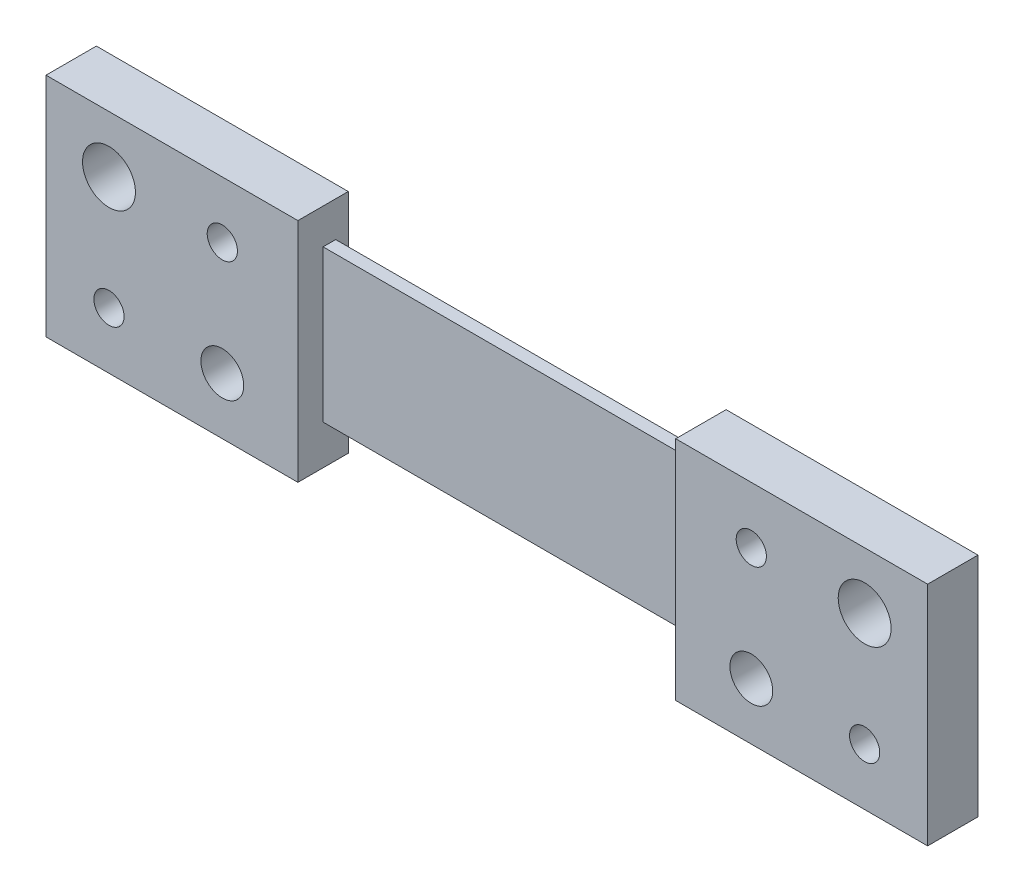
SolidWorks part; units mm, degrees
ref_plane "Спереди" through (0, 0, 0) normal (0, 0, 1) x (1, 0, 0)
ref_plane "Сверху" through (0, 0, 0) normal (0, 1, 0) x (1, 0, 0)
ref_plane "Справа" through (0, 0, 0) normal (1, 0, 0) x (0, 0, -1)
sketch "Эскиз1" plane through (0, 0, 0) normal (0, 0, 1) x (1, 0, 0)
  line L0 (-42.678, 0) -> (49.8614, 0) construction
  line L1 (0, 35.1777) -> (0, -24.4025) construction
  line L2 (15, -9) -> (15, 9)
  line L3 (-35, -9) -> (-15, -9)
  line L4 (-35, -9) -> (-35, 9)
  line L5 (-35, 9) -> (-15, 9)
  line L6 (-15, -9) -> (-15, 9)
  line L7 (35, 9) -> (15, 9)
  line L8 (35, -9) -> (35, 9)
  line L9 (35, -9) -> (15, -9)
  circle A0 centre (-30, 4.5) radius 2.1
  circle A1 centre (-21, 4.5) radius 1.2
  circle A2 centre (-21, -4.5) radius 1.7
  circle A3 centre (-30, -4.5) radius 1.2
  circle A4 centre (30, -4.5) radius 1.2
  circle A5 centre (21, -4.5) radius 1.7
  circle A6 centre (21, 4.5) radius 1.2
  circle A7 centre (30, 4.5) radius 2.1
  dimension "D4" = 4.5
  dimension "D6" = 4.2
  dimension "D7" = 6
  dimension "D8" = 4.5
  dimension "D9" = 2.4
  dimension "D11" = 4.5
  dimension "D12" = 6
  dimension "D13" = 4.5
  dimension "D14" = 3.4
  dimension "D1" = 20
  dimension "D2" = 18
  dimension "D3" = 35
  dimension "D5" = 5
  dimension "D10" = 5
extrude "Вытянуть1" add sketch "Эскиз1" along normal blind 4
cosmetic thread "Условное изображение резьбы1" parameters "D2"=3
cosmetic thread "Условное изображение резьбы2" parameters "D2"=3
cosmetic thread "Условное изображение резьбы3" parameters "D2"=3
cosmetic thread "Условное изображение резьбы4" parameters "D2"=3
cosmetic thread "Условное изображение резьбы5" parameters "D2"=4
cosmetic thread "Условное изображение резьбы6" parameters "D2"=4
cosmetic thread "Условное изображение резьбы7" parameters "D2"=5
cosmetic thread "Условное изображение резьбы8" parameters "D2"=5
ref_plane "Плоскость1" through (0, 0, 2) normal (0, 0, -1) x (-1, 0, 0)
sketch "Эскиз2" plane through (0, 0, 2) normal (0, 0, -1) x (-1, 0, 0)
  line L1 (-16.5252, -5.8577) -> (16.5981, -5.8577)
  line L2 (-16.5252, -5.8577) -> (-16.5252, 6.1948)
  line L3 (-16.5252, 6.1948) -> (16.5981, 6.1948)
  line L4 (16.5981, -5.8577) -> (16.5981, 6.1948)
extrude "Вытянуть2" add sketch "Эскиз2" along normal blind 1
